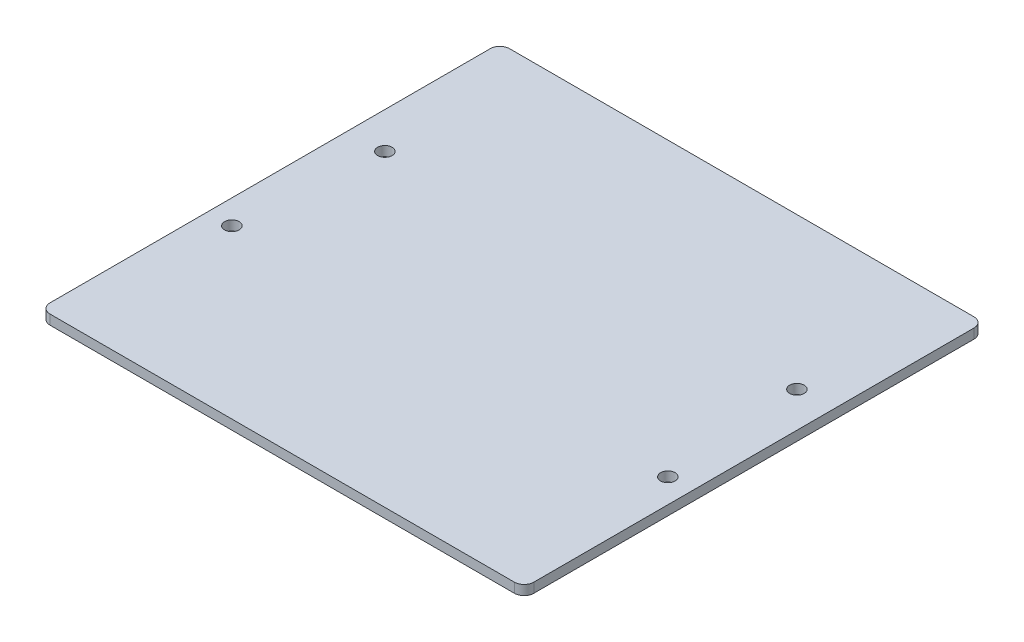
SolidWorks part; units mm, degrees
material "PBT 一般用途"
ref_plane "前视基准面" through (0, 0, 0) normal (0, 0, 1) x (1, 0, 0)
ref_plane "上视基准面" through (0, 0, 0) normal (0, 1, 0) x (1, 0, 0)
ref_plane "右视基准面" through (0, 0, 0) normal (1, 0, 0) x (0, 0, -1)
sketch "草图1" plane through (0, 0, 0) normal (0, 1, 0) x (1, 0, 0)
  line L1 (-50, -47.5) -> (50, -47.5)
  line L2 (-50, -47.5) -> (-50, 47.5)
  line L3 (-50, 47.5) -> (50, 47.5)
  line L4 (50, -47.5) -> (50, 47.5)
  line L5 (-50, -47.5) -> (50, 47.5) construction
  line L6 (-50, 47.5) -> (50, -47.5) construction
  point P0 (0, 0)
  dimension "D1" = 100
  dimension "D2" = 95
extrude "凸台-拉伸1" add sketch "草图1" along normal blind 2
sketch "草图2" plane through (0, 2, 0) normal (0, 1, 0) x (1, 0, 0)
  line L0 (-50, 47.5) -> (-50, -47.5) construction
  line L1 (-50, -47.5) -> (50, -47.5) construction
  line L2 (50, 47.5) -> (-50, 47.5) construction
  line L3 (50, -47.5) -> (50, 47.5) construction
  point P0 (-45, -12.906)
  point P5 (-42.5, 16.216)
  point P8 (42.673, 16.216)
  point P11 (45, -12.784)
  dimension "D1" = 5
  dimension "D2" = 34.594
  dimension "D3" = 7.5
  dimension "D4" = 31.284
  dimension "D5" = 7.327
  dimension "D6" = 31.284
  dimension "D7" = 34.716
  dimension "D8" = 5
hole_wizard "孔1" positions "草图2" profile "草图5" legacy end condition up to next
sketch "草图5" plane through (-45, 2, 12.906) normal (1, 0, 0) x (0, 0, 1)
  line L0 (0, 0) -> (0, 2)
  line L1 (0, 2) -> (1.5, 2)
  line L2 (1.5, 2) -> (1.5, 0)
  line L3 (1.5, 0) -> (0, 0)
  line L4 (0, 110) -> (0, -10) construction
  dimension "直径" = 3
  dimension "深度" = 2
fillet "圆角1" radius 2 4 edges at (-50, 1, -47.5) (50, 1, -47.5) (50, 1, 47.5) (-50, 1, 47.5)
